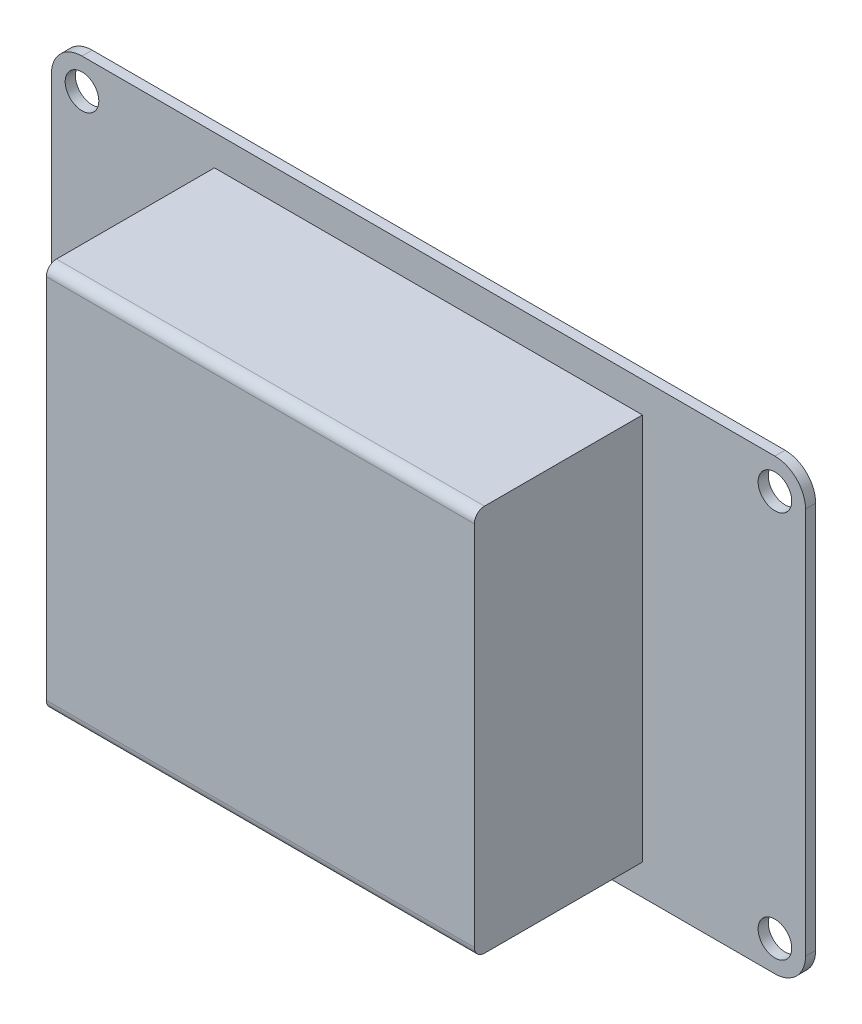
SolidWorks part; units mm, degrees
ref_plane "Alzado" through (0, 0, 0) normal (1, 0, 0) x (0, 1, 0)
ref_plane "Planta" through (0, 0, 0) normal (0, 0, 1) x (0, 1, 0)
ref_plane "Vista lateral" through (0, 0, 0) normal (0, 1, 0) x (-1, 0, 0)
sketch "Croquis1" plane through (0, 0, 0) normal (0, 0, 1) x (0, 1, 0)
  line L1 (-19, -37) -> (19, -37)
  line L2 (-22, -34) -> (-22, 34)
  line L3 (-19, 37) -> (19, 37)
  line L4 (22, -34) -> (22, 34)
  line L5 (-22, -37) -> (22, 37) construction
  line L6 (-22, 37) -> (22, -37) construction
  arc A0 (-19, -37) -> (-22, -34) centre (-19, -34) cw
  arc A1 (19, -37) -> (22, -34) centre (19, -34) ccw
  arc A2 (19, 37) -> (22, 34) centre (19, 34) cw
  arc A3 (-22, 34) -> (-19, 37) centre (-19, 34) cw
  circle A4 centre (-19, 34) radius 1.65
  circle A5 centre (19, 34) radius 1.65
  circle A6 centre (19, -34) radius 1.65
  circle A7 centre (-19, -34) radius 1.65
  point P0 (0, 0)
  point P19 (0, 0)
  point P20 (0, 0)
  dimension "D3" = 3
  dimension "D6" = 3.3
  dimension "D1" = 44
  dimension "D2" = 74
  dimension "D4" = 2
  dimension "D5" = 2
extrude "Saliente-Extruir1" add sketch "Croquis1" along normal blind 1
sketch "Croquis3" plane through (0, 0, 1) normal (0, 0, 1) x (1, 0, 0)
  line L1 (-21, -19) -> (21, -19)
  line L2 (-21, -19) -> (-21, 19)
  line L3 (-21, 19) -> (21, 19)
  line L4 (21, -19) -> (21, 19)
  line L5 (-21, -19) -> (21, 19) construction
  line L6 (-21, 19) -> (21, -19) construction
  point P0 (0, 0)
  dimension "D1" = 42
extrude "Saliente-Extruir2" add sketch "Croquis3" along normal blind 16.5
fillet "Redondeo1" radius 1 2 edges at (0, 19, 17.5) (0, -19, 17.5)
